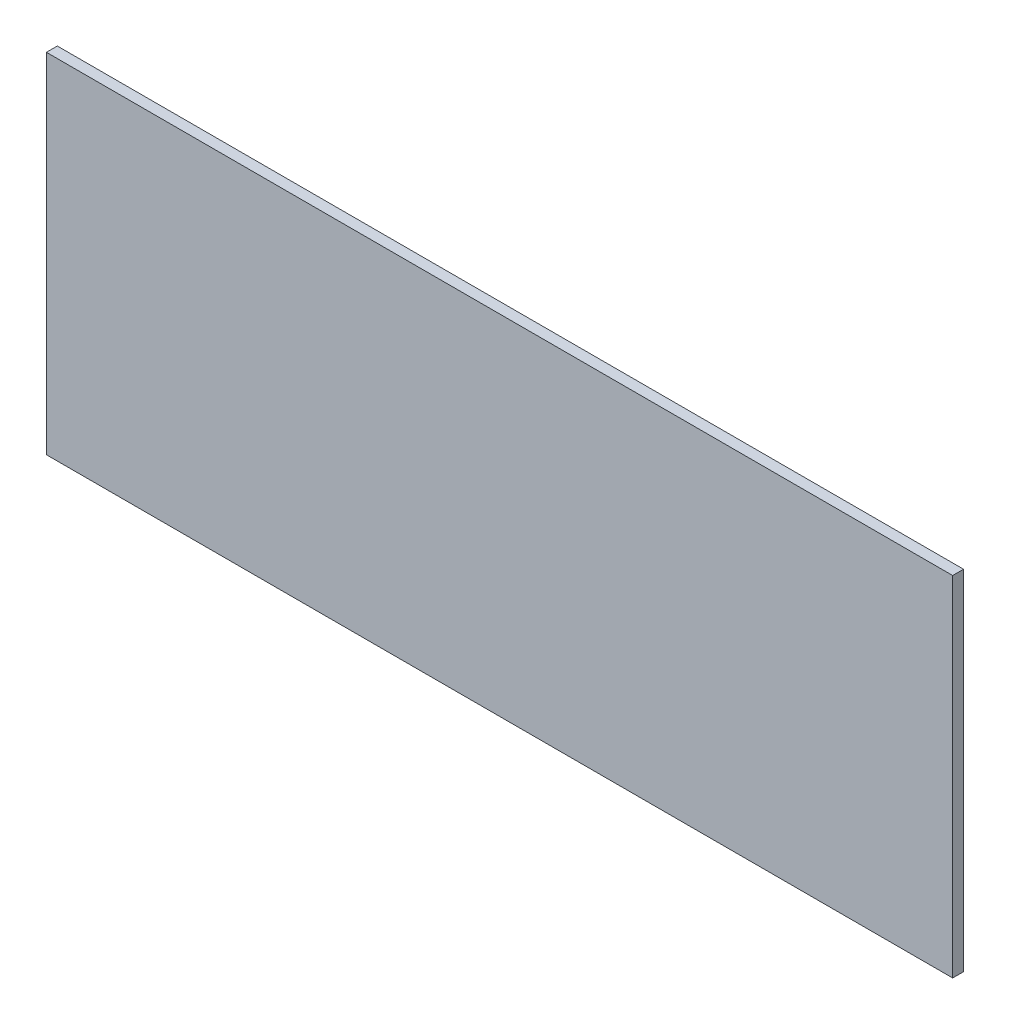
SolidWorks part; units mm, degrees
ref_plane "Plan de face" through (0, 0, 0) normal (0, 0, 1) x (1, 0, 0)
ref_plane "Plan de dessus" through (0, 0, 0) normal (0, 1, 0) x (1, 0, 0)
ref_plane "Plan de droite" through (0, 0, 0) normal (1, 0, 0) x (0, 0, -1)
sketch "Esquisse1" plane through (0, 0, 0) normal (0, 0, 1) x (1, 0, 0)
  line L1 (-416, -160) -> (416, -160)
  line L2 (-416, -160) -> (-416, 160)
  line L3 (-416, 160) -> (416, 160)
  line L4 (416, -160) -> (416, 160)
  line L5 (-416, -160) -> (416, 160) construction
  line L6 (-416, 160) -> (416, -160) construction
  point P0 (0, 0)
  dimension "D1" = 832
  dimension "D2" = 320
extrude "Boss.-Extru.1" add sketch "Esquisse1" along normal blind 10
